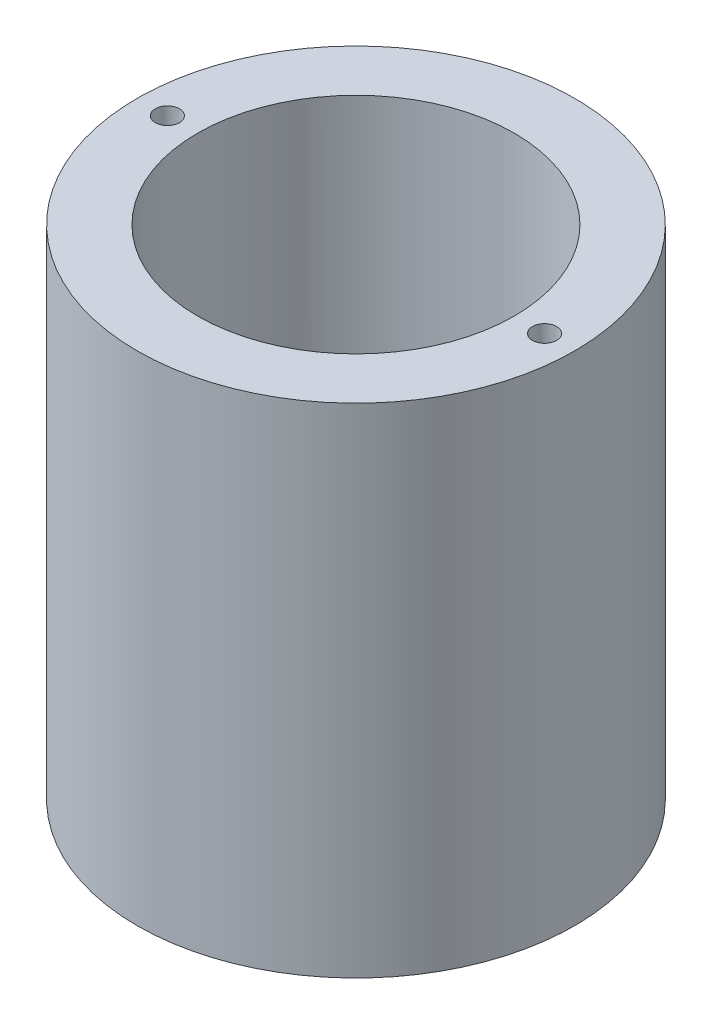
SolidWorks part; units mm, degrees
ref_plane "Спереди" through (0, 0, 0) normal (0, 0, 1) x (1, 0, 0)
ref_plane "Сверху" through (0, 0, 0) normal (0, 1, 0) x (1, 0, 0)
ref_plane "Справа" through (0, 0, 0) normal (1, 0, 0) x (0, 0, -1)
sketch "Эскиз1" plane through (0, 0, 0) normal (0, 1, 0) x (1, 0, 0)
  circle A0 centre (0, 0) radius 9.172
  circle A1 centre (0, 0) radius 13
extrude "Бобышка-Вытянуть1" add sketch "Эскиз1" along normal blind 25
sketch "Эскиз7" plane through (0, 0, 0) normal (0, -1, 0) x (1, 0, 0)
  circle A0 centre (0, 0) radius 10.172
extrude "Вырез-Вытянуть2" cut sketch "Эскиз7" against normal blind 50
sketch "Эскиз8" plane through (0, 25, 0) normal (0, 1, 0) x (1, 0, 0)
  circle A0 centre (0, 0) radius 13
  circle A1 centre (0, 0) radius 10.172
extrude "Бобышка-Вытянуть2" add sketch "Эскиз8" along normal blind 8
sketch "Эскиз11" plane through (0, 0, 0) normal (0, -1, 0) x (1, 0, 0)
  circle A0 centre (0, 0) radius 10.5
extrude "Вырез-Вытянуть4" cut sketch "Эскиз11" against normal blind 50
cosmetic thread "Условное изображение резьбы5" parameters "D2"=22
sketch "Эскиз13" plane through (0, 33, 0) normal (0, 1, 0) x (1, 0, 0)
  circle A0 centre (0, 0) radius 14.5
  circle A1 centre (0, 0) radius 13
extrude "Бобышка-Вытянуть3" add sketch "Эскиз13" against normal blind 33
sketch "Эскиз4" plane through (0, 0, 0) normal (1, 0, 0) x (0, 0, -1)
  circle A0 centre (0, 10) radius 0.8
extrude "Вырез-Вытянуть1" cut sketch "Эскиз4" against normal blind 30
cosmetic thread "Условное изображение резьбы2" parameters "D2"=2
sketch "Эскиз10" plane through (0, 33, 0) normal (0, 1, 0) x (1, 0, 0)
  circle A2 centre (-12.5, 0) radius 0.8
  circle A4 centre (12.5, 0) radius 0.8
extrude "Вырез-Вытянуть5" cut sketch "Эскиз10" against normal blind 7
cosmetic thread "Условное изображение резьбы6" parameters "D1"=6, "D2"=2
cosmetic thread "Условное изображение резьбы7" parameters "D1"=6, "D2"=2
